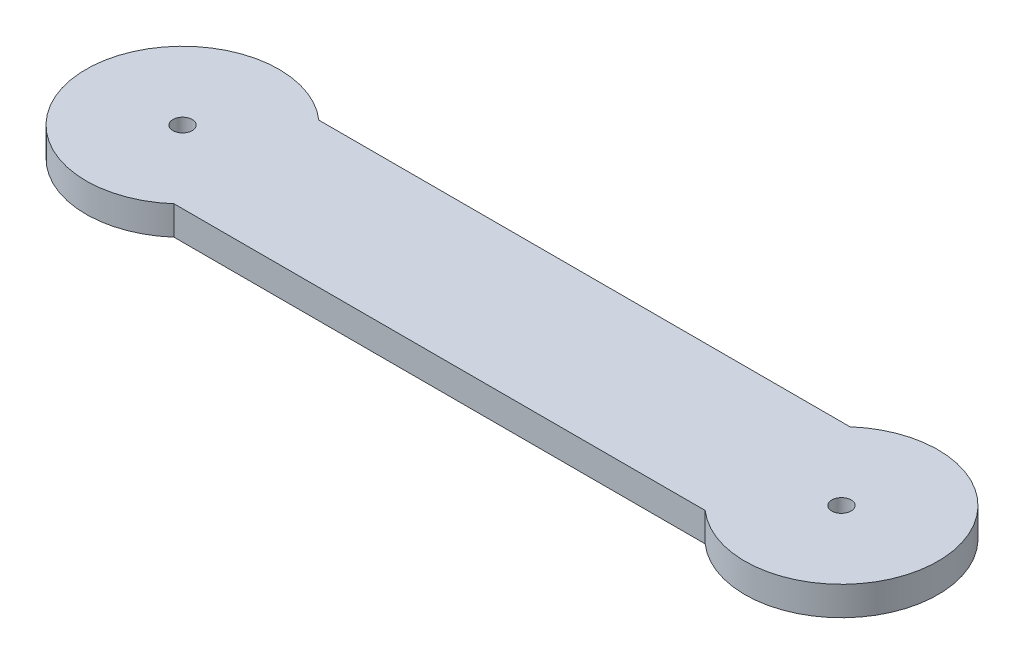
SolidWorks part; units mm, degrees
ref_plane "Front Plane" through (0, 0, 0) normal (0, 0, 1) x (1, 0, 0)
ref_plane "Top Plane" through (0, 0, 0) normal (0, 1, 0) x (1, 0, 0)
ref_plane "Right Plane" through (0, 0, 0) normal (1, 0, 0) x (0, 0, -1)
sketch "Sketch1" plane through (0, 0, 0) normal (0, 1, 0) x (1, 0, 0)
  line L1 (0, 0) -> (-55, 0)
  line L3 (0, 15) -> (-55, 15)
  arc A0 (0, 15) -> (0, 0) centre (6.6144, 7.5) cw
  arc A1 (-55, 15) -> (-55, 0) centre (-61.6144, 7.5) ccw
  dimension "D3" = 10
  dimension "D4" = 10
  dimension "D2" = 15
extrude "Boss-Extrude1" add sketch "Sketch1" along normal blind 3
sketch "Sketch2" plane through (0, 3, 0) normal (0, 1, 0) x (1, 0, 0)
  circle A0 centre (-61.6144, 7.5) radius 1
  circle A1 centre (6.6144, 7.5) radius 1
  dimension "D1" = 2
  dimension "D2" = 2
extrude "Cut-Extrude1" cut sketch "Sketch2" against normal blind 23
